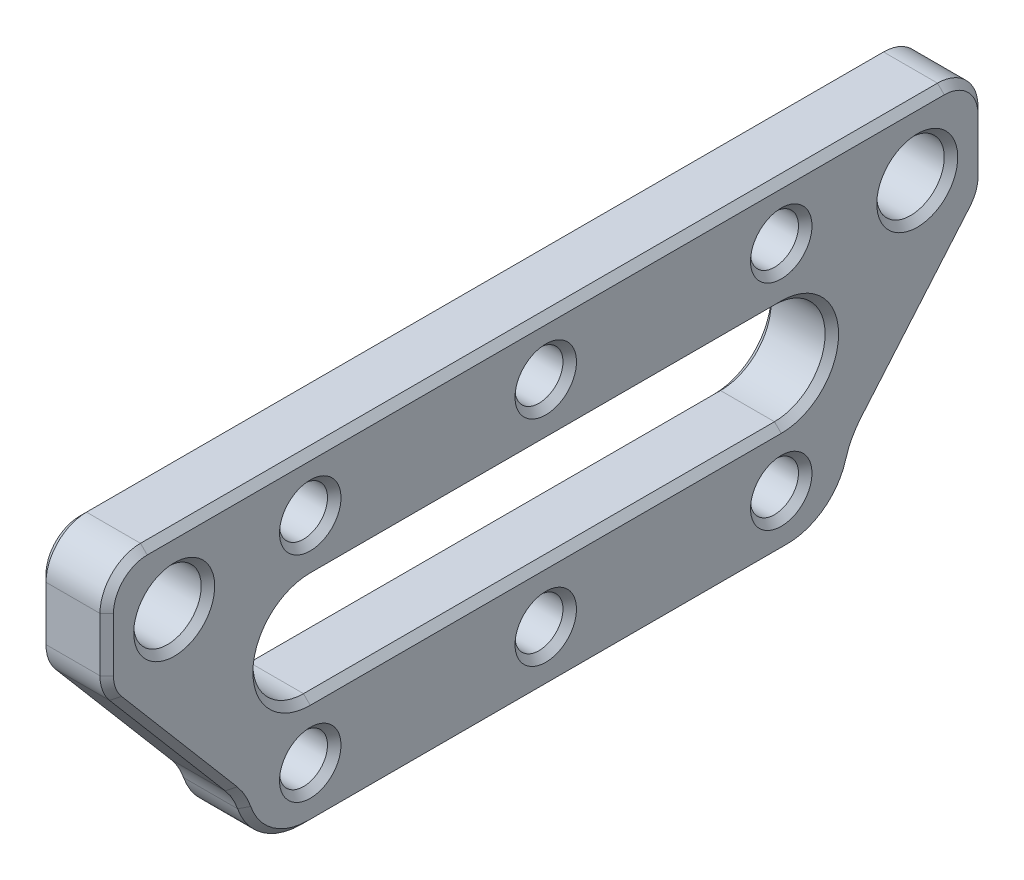
SolidWorks part; units mm, degrees
ref_plane "Front Plane" through (0, 0, 0) normal (0, 0, 1) x (1, 0, 0)
ref_plane "Top Plane" through (0, 0, 0) normal (0, 1, 0) x (1, 0, 0)
ref_plane "Right Plane" through (0, 0, 0) normal (1, 0, 0) x (0, 0, -1)
ref_plane "Plane1" through (-8.175, 0, 0) normal (-1, 0, 0) x (0, -1, 0)
sketch "Sketch1" plane through (-8.175, 0, 0) normal (-1, 0, 0) x (0, -1, 0)
  line L0 (24, -96.03) -> (24, -30.97)
  line L1 (24, -30.97) -> (0, -30.97)
  line L2 (0, -30.97) -> (0, -96.03)
  line L3 (0, -96.03) -> (24, -96.03)
extrude "Boss-Extrude1" add sketch "Sketch1" against normal blind 5
sketch "Sketch2" plane through (-3.175, 0, 0) normal (1, 0, 0) x (0, 0, -1)
  line L0 (30.97, -24) -> (45.8928, -24)
  line L1 (40.2524, -19.0302) -> (30.97, -8.1021)
  line L2 (30.97, -8.1021) -> (30.97, -24)
  arc A0 (45.8928, -24) -> (41.1672, -20.6336) centre (45.8928, -19) cw
  arc A1 (41.1672, -20.6336) -> (40.2524, -19.0302) centre (36.4416, -22.2671) ccw
extrude "Cut-Extrude1" cut sketch "Sketch2" against normal through all
sketch "Sketch3" plane through (-3.175, 0, 0) normal (1, 0, 0) x (0, 0, -1)
  line L0 (81.4047, -24) -> (96.03, -24)
  line L1 (96.03, -24) -> (96.03, -8.1021)
  line L2 (96.03, -8.1021) -> (87.2192, -18.475)
  arc A0 (87.2192, -18.475) -> (86.2174, -20.356) centre (91.03, -21.7119) ccw
  arc A1 (86.2174, -20.356) -> (81.4047, -24) centre (81.4047, -19) cw
extrude "Cut-Extrude2" cut sketch "Sketch3" against normal through all
sketch "Sketch4" plane through (-3.175, 0, 0) normal (1, 0, 0) x (0, 0, -1)
  line L0 (80.95, -8.1875) -> (46.05, -8.1875)
  line L1 (46.05, -15.6875) -> (80.95, -15.6875)
  arc A0 (80.95, -15.6875) -> (80.95, -8.1875) centre (80.95, -11.9375) ccw
  arc A1 (46.05, -8.1875) -> (46.05, -15.6875) centre (46.05, -11.9375) ccw
extrude "Cut-Extrude3" cut sketch "Sketch4" against normal through all
hole_wizard "M3 Clearance Hole1" positions "Sketch6" profile "Sketch5" hole size "M3" standard "ANSI Metric"
sketch "Sketch6" plane through (-8.175, 0, 0) normal (-1, 0, 0) x (0, 0, 1)
  point P0 (-46.05, -4)
sketch "Sketch5" plane through (-8.175, -4, -46.05) normal (0, 1, 0) x (0, 0, 1)
  line L0 (0, 0) -> (0, 5)
  line L1 (0, 5) -> (1.778, 5)
  line L2 (1.778, 5) -> (1.778, 0)
  line L5 (1.778, 0) -> (0, 0)
  line L11 (0, -6.35) -> (0, 107.95) construction
  dimension "Thru Hole Dia." = 3.556
  dimension "Thru Hole Depth" = 5
hole_wizard "M3 Clearance Hole2" positions "Sketch8" profile "Sketch7" hole size "M3" standard "ANSI Metric"
sketch "Sketch8" plane through (-3.175, 0, 0) normal (1, 0, 0) x (0, 0, -1)
  point P0 (46.05, -19.875)
  point P1 (63.5, -19.875)
  point P2 (80.95, -19.875)
  point P3 (80.95, -4)
  point P4 (63.5, -4)
sketch "Sketch7" plane through (-3.175, -19.875, -46.05) normal (0, 1, 0) x (0, 0, -1)
  line L0 (0, 0) -> (0, 5)
  line L1 (0, 5) -> (1.778, 5)
  line L2 (1.778, 5) -> (1.778, 0)
  line L5 (1.778, 0) -> (0, 0)
  line L11 (0, -6.35) -> (0, 107.95) construction
  dimension "Thru Hole Dia." = 3.556
  dimension "Thru Hole Depth" = 5
hole_wizard "Ø5.0 (5) Diameter Hole1" positions "Sketch10" profile "Sketch9" hole size "Ø5.0" standard "ANSI Metric"
sketch "Sketch10" plane through (-8.175, 0, 0) normal (-1, 0, 0) x (0, 0, 1)
  point P0 (-91.03, -5)
sketch "Sketch9" plane through (-8.175, -5, -91.03) normal (0, 1, 0) x (0, 0, 1)
  line L0 (0, 0) -> (0, 5)
  line L1 (0, 5) -> (2.5, 5)
  line L2 (2.5, 5) -> (2.5, 0)
  line L5 (2.5, 0) -> (0, 0)
  line L11 (0, -6.35) -> (0, 107.95) construction
  dimension "Thru Hole Dia." = 5
  dimension "Thru Hole Depth" = 5
hole_wizard "Ø5.0 (5) Diameter Hole2" positions "Sketch12" profile "Sketch11" hole size "Ø5.0" standard "ANSI Metric"
sketch "Sketch12" plane through (-3.175, 0, 0) normal (1, 0, 0) x (0, 0, -1)
  point P0 (35.97, -5)
sketch "Sketch11" plane through (-3.175, -5, -35.97) normal (0, 1, 0) x (0, 0, -1)
  line L0 (0, 0) -> (0, 5)
  line L1 (0, 5) -> (2.5, 5)
  line L2 (2.5, 5) -> (2.5, 0)
  line L5 (2.5, 0) -> (0, 0)
  line L11 (0, -6.35) -> (0, 107.95) construction
  dimension "Thru Hole Dia." = 5
  dimension "Thru Hole Depth" = 5
fillet "Fillet1" radius 3 4 edges at (-5.675, -8.1021, -30.97) (-5.675, 0, -96.03) (-5.675, 0, -30.97) (-5.675, -8.1021, -96.03)
chamfer "Chamfer1" distance 0.5 angle 45 52 edges at (-3.175, -0.8787, -31.8487) (-3.175, 0, -63.5) (-3.175, -5, -30.97) (-3.175, -0.8787, -95.1513) (-3.175, -8.0345, -31.154) (-3.175, -5, -96.03) (-3.175, -13.9862, -35.968) (-3.175, -8.0345, -95.846) (-3.175, -19.7893, -40.7845) (-3.175, -13.7086, -91.2678) (-3.175, -23.0723, -42.9918) (-3.175, -19.3615, -86.6169) (-3.175, -24, -63.6488) (-3.175, -22.9862, -84.423) (-8.175, -19.875, -47.828) (-3.175, -4, -44.272) (-8.175, -19.875, -82.728) (-8.175, -4, -82.728) (-3.175, -8.1875, -63.5) (-3.175, -11.9375, -84.7) (-3.175, -11.9375, -42.3) (-3.175, -15.6875, -63.5) (-8.175, -4, -65.278) (-3.175, -4, -65.278) (-8.175, 0, -63.5) (-8.175, -0.8787, -95.1513) (-8.175, -0.8787, -31.8487) (-8.175, -5, -96.03) (-8.175, -5, -30.97) (-8.175, -8.0345, -95.846) (-8.175, -8.0345, -31.154) (-8.175, -13.7086, -91.2678) (-8.175, -13.9862, -35.968) (-8.175, -19.3615, -86.6169) (-8.175, -19.7893, -40.7845) (-8.175, -22.9862, -84.423) (-8.175, -23.0723, -42.9918) (-8.175, -24, -63.6488) (-3.175, -5, -88.53) (-3.175, -19.875, -82.728) (-8.175, -5, -38.47) (-8.175, -19.875, -65.278) (-3.175, -5, -38.47) (-3.175, -19.875, -47.828) (-3.175, -19.875, -65.278) (-3.175, -4, -82.728) (-8.175, -15.6875, -63.5) (-8.175, -11.9375, -84.7) (-8.175, -11.9375, -42.3) (-8.175, -8.1875, -63.5) (-8.175, -5, -88.53) (-8.175, -4, -44.272)
